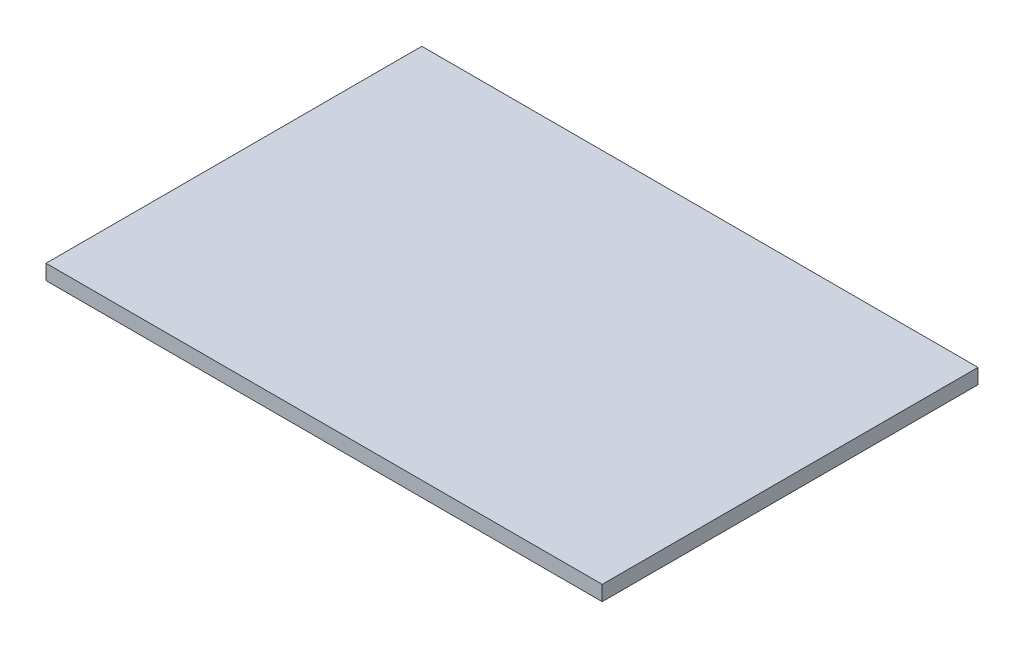
SolidWorks part; units mm, degrees
ref_plane "Ön Düzlem" through (0, 0, 0) normal (0, 0, 1) x (1, 0, 0)
ref_plane "Üst Düzlem" through (0, 0, 0) normal (0, 1, 0) x (1, 0, 0)
ref_plane "Sağ Düzlem" through (0, 0, 0) normal (1, 0, 0) x (0, 0, -1)
sketch "Çizim2" plane through (0, 0, 0) normal (0, 1, 0) x (1, 0, 0)
  line L0 (0, 144.1483) -> (0, -135.9108) construction
  line L2 (-132.0738, 128.9748) -> (237.9262, 128.9748)
  line L3 (-132.0738, 128.9748) -> (-132.0738, -121.0252)
  line L4 (-132.0738, -121.0252) -> (237.9262, -121.0252)
  line L5 (237.9262, 128.9748) -> (237.9262, -121.0252)
  dimension "D1" = 370
  dimension "D2" = 250
extrude "Yükseklik-Ekstrüzyon1" add sketch "Çizim2" along normal blind 10
